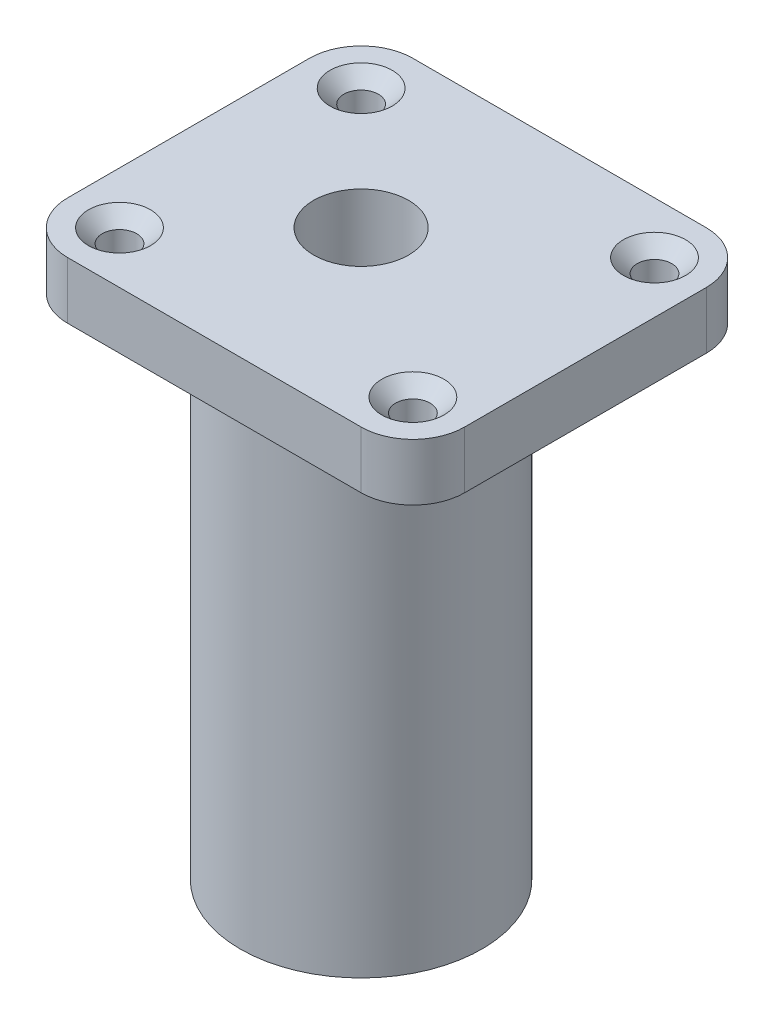
SolidWorks part; units mm, degrees
ref_plane "Front Plane" through (0, 0, 0) normal (0, 0, 1) x (1, 0, 0)
ref_plane "Top Plane" through (0, 0, 0) normal (0, 1, 0) x (1, 0, 0)
ref_plane "Right Plane" through (0, 0, 0) normal (1, 0, 0) x (0, 0, -1)
sketch "Sketch1" plane through (0, 0, 0) normal (0, 1, 0) x (1, 0, 0)
  circle A0 centre (0, 0) radius 7
  dimension "D1" = 14
extrude "Boss-Extrude1" add sketch "Sketch1" along normal blind 32.7
sketch "Sketch2" plane through (0, 0, 0) normal (0, -1, 0) x (1, 0, 0)
  circle A0 centre (0, 0) radius 4.6
  dimension "D1" = 9.2
sketch "Sketch4" plane through (0, 32.7, 0) normal (0, 1, 0) x (1, 0, 0)
  line L0 (-10, 10) -> (13, 10)
  line L2 (-10, 10) -> (-10, -10)
  line L3 (-10, -10) -> (13, -10)
  line L4 (13, 10) -> (13, -10)
  circle A0 centre (0, 0) radius 3.5
  dimension "D1" = 10
  dimension "D2" = 10
  dimension "D3" = 10
  dimension "D4" = 13
extrude "Boss-Extrude2" add sketch "Sketch4" against normal blind 3.3
fillet "Fillet1" radius 3 4 edges at (-10, 31.05, 10) (13, 31.05, 10) (13, 31.05, -10) (-10, 31.05, -10)
sketch "Sketch5" plane through (0, 32.7, 0) normal (0, 1, 0) x (1, 0, 0)
  circle A0 centre (-7, 7) radius 1
  circle A1 centre (10, 7) radius 1
  circle A2 centre (10, -7) radius 1
  circle A3 centre (-7, -7) radius 1
  dimension "D1" = 2
  dimension "D2" = 2
  dimension "D3" = 2
extrude "Cut-Extrude3" cut sketch "Sketch5" against normal blind 5
extrude "Cut-Extrude4" cut sketch "Sketch2" against normal blind 5
sketch "Sketch6" plane through (0, 5, 0) normal (0, -1, 0) x (1, 0, 0)
  circle A0 centre (0, 0) radius 2.75
  dimension "D1" = 5.5
extrude "Cut-Extrude5" cut sketch "Sketch6" against normal blind 36
fillet "Fillet2" radius 1 1 edges at (0, 29.4, 7)
chamfer "Chamfer1" distance 0.8 angle 45 4 edges at (-7, 32.7, 8) (10, 32.7, 8) (10, 32.7, -6) (-7, 32.7, -6)
